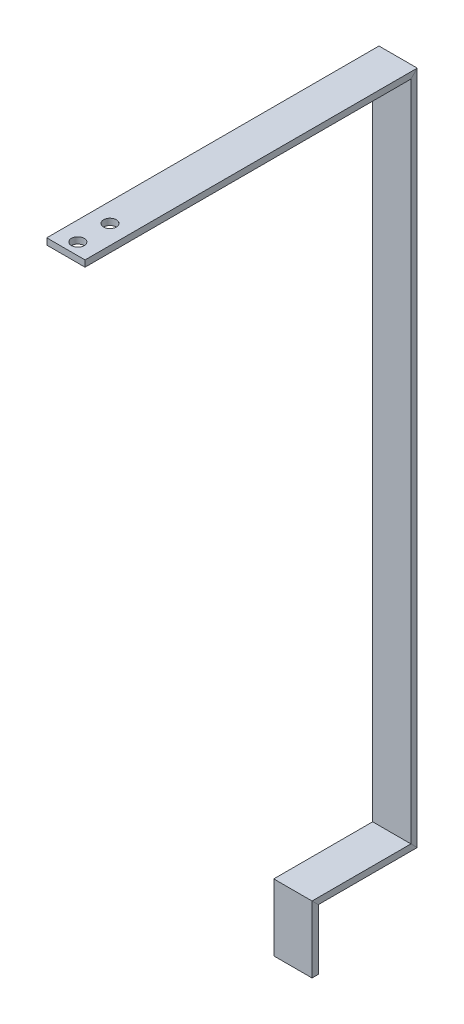
SolidWorks part; units mm, degrees
ref_plane "Alzado" through (0, 0, 0) normal (0, 0, 1) x (1, 0, 0)
ref_plane "Planta" through (0, 0, 0) normal (0, 1, 0) x (1, 0, 0)
ref_plane "Vista lateral" through (0, 0, 0) normal (1, 0, 0) x (0, 0, -1)
sketch "Croquis1" plane through (0, 0, 0) normal (0, 0, 1) x (1, 0, 0)
  line L1 (-19.05, 425.25) -> (19.05, 425.25)
  line L2 (-19.05, 425.25) -> (-19.05, -425.25)
  line L3 (-19.05, -425.25) -> (19.05, -425.25)
  line L4 (19.05, 425.25) -> (19.05, -425.25)
  line L5 (-19.05, 425.25) -> (19.05, -425.25) construction
  line L6 (-19.05, -425.25) -> (19.05, 425.25) construction
  point P0 (0, 0)
  dimension "D1" = 38.1
  dimension "D2" = 850.5
extrude "Saliente-Extruir1" add sketch "Croquis1" along normal blind 6.31
sketch "Croquis2" plane through (0, 0, 6.31) normal (0, 0, 1) x (1, 0, 0)
  line L0 (-19.05, -425.25) -> (19.05, -425.25) construction
  line L1 (-19.05, -418.94) -> (19.05, -418.94)
  line L2 (-19.05, -418.94) -> (-19.05, -425.25)
  line L3 (-19.05, -425.25) -> (19.05, -425.25)
  line L4 (19.05, -418.94) -> (19.05, -425.25)
  line L5 (-19.05, -418.94) -> (19.05, -425.25) construction
  line L6 (-19.05, -425.25) -> (19.05, -418.94) construction
  line L7 (-19.05, 425.25) -> (-19.05, -425.25) construction
  point P0 (0, -422.095)
  dimension "D1" = 6.31
extrude "Saliente-Extruir2" add sketch "Croquis2" along normal blind 70
sketch "Croquis3" plane through (0, 0, 6.31) normal (0, 0, 1) x (1, 0, 0)
  line L0 (-19.05, -425.25) -> (-19.05, -274.75) construction
  line L1 (-19.05, 425.25) -> (-19.05, -418.94) construction
  line L2 (19.05, -418.94) -> (19.05, 425.25) construction
  line L3 (-19.05, -262.4761) -> (19.05, -262.4761)
  line L4 (-19.05, -262.4761) -> (-19.05, -268.7861)
  line L5 (-19.05, -268.7861) -> (19.05, -268.7861)
  line L6 (19.05, -262.4761) -> (19.05, -268.7861)
  line L7 (-19.05, -262.4761) -> (19.05, -268.7861) construction
  line L8 (-19.05, -268.7861) -> (19.05, -262.4761) construction
  point P5 (0, -265.6311)
  dimension "D1" = 150.5
  dimension "D2" = 6.31
  dimension "D3" = 38.1
extrude "Saliente-Extruir3" add sketch "Croquis3" against normal blind 578
sketch "Croquis4" plane through (0, -262.4761, 0) normal (0, 1, 0) x (1, 0, 0)
  circle A0 centre (0, 536.9815) radius 6.9359
extrude "Cortar-Extruir1" cut sketch "Croquis4" against normal blind 7
sketch "Croquis5" plane through (0, 0, 0) normal (0, 0, -1) x (-1, 0, 0)
  line L0 (-19.05, 425.25) -> (19.05, 425.25)
  line L1 (19.05, 425.25) -> (19.05, -262.4761)
  line L2 (19.05, -262.4761) -> (-19.05, -262.4761)
  line L3 (-19.05, -262.4761) -> (-19.05, 425.25)
extrude "Cortar-Extruir2" cut sketch "Croquis5" against normal blind 10
sketch "Croquis6" plane through (0, -262.4761, 0) normal (0, 1, 0) x (1, 0, 0)
  line L0 (0, -6.31) -> (0, 196.49) construction
  line L1 (19.05, -6.31) -> (-19.05, -6.31) construction
  line L2 (19.05, 202.8) -> (-19.05, 202.8)
  line L3 (19.05, 571.69) -> (19.05, -6.31) construction
  line L4 (-19.05, 571.69) -> (-19.05, -6.31) construction
  line L5 (-19.05, 202.8) -> (-19.05, 196.49)
  line L6 (-19.05, 196.49) -> (19.05, 196.49)
  line L7 (19.05, 196.49) -> (19.05, 202.8)
  line L8 (19.05, 202.8) -> (-19.05, 196.49) construction
  line L9 (-19.05, 202.8) -> (19.05, 196.49) construction
  dimension "D1" = 202.8
  dimension "D2" = 6.31
sketch3d "Croquis3D1"
  line L0 (0, -262.4761, -199.645) -> (0, 386.8539, -199.645)
  line L1 (19.05, -262.4761, -202.8) -> (-19.05, -262.4761, -196.49) construction
  line L2 (0, 386.8539, -199.645) -> (0, 386.8539, 127.905)
  dimension "D1" = 649.33
  dimension "D2" = 327.55
sweep "Barrer1" add profiles "Croquis6" path "Croquis3D1"
sketch "Croquis8" plane through (19.05, 0, 0) normal (1, 0, 0) x (0, 0, -1)
  line L0 (196.49, -262.4761) -> (196.49, -268.7861)
  line L1 (571.69, -268.7861) -> (0, -268.7861) construction
  line L2 (196.49, -268.7861) -> (196.49, -444.3077)
  line L3 (196.49, -444.3077) -> (-90.8346, -444.3077)
  line L4 (-90.8346, -444.3077) -> (-90.8346, -262.4761)
  line L5 (-90.8346, -262.4761) -> (196.49, -262.4761)
  line L6 (202.8, -262.4761) -> (202.8, -268.7861)
  line L7 (202.8, -268.7861) -> (571.69, -268.7861)
  line L8 (571.69, -268.7861) -> (571.69, -262.4761)
  line L9 (571.69, -262.4761) -> (202.8, -262.4761)
extrude "Cortar-Extruir3" cut sketch "Croquis8" against normal blind 147
sketch "Croquis9" plane through (0, 390.0089, 0) normal (0, 1, 0) x (1, 0, 0)
  circle A0 centre (0, -84.01) radius 6.35
  circle A1 centre (0, -116.01) radius 6.35
extrude "Cortar-Extruir4" cut sketch "Croquis9" against normal blind 6.31
sketch "Croquis10" plane through (0, -268.7861, 0) normal (0, -1, 0) x (1, 0, 0)
  line L0 (-19.05, -202.8) -> (-19.05, -196.49)
  line L1 (-19.05, -196.49) -> (19.05, -196.49)
  line L2 (19.05, -196.49) -> (19.05, -202.8)
  line L3 (19.05, -202.8) -> (-19.05, -202.8)
  line L4 (0, -196.49) -> (0, -202.8) construction
  line L5 (0, -202.8) -> (0, -199.645) construction
  line L6 (0, -199.645) -> (5.7421, -199.645) construction
sketch3d "Croquis3D2"
  line L0 (0, -268.7861, -199.645) -> (0, -278.7861, -199.645)
  line L1 (0, -278.7861, -199.645) -> (0, -278.7861, -101.215)
  line L2 (0, -278.7861, -101.215) -> (0, -342.0261, -101.215)
  dimension "D1" = 10
  dimension "D2" = 98.43
  dimension "D3" = 63.24
sweep "Barrer2" add profiles "Croquis10" path "Croquis3D2"
